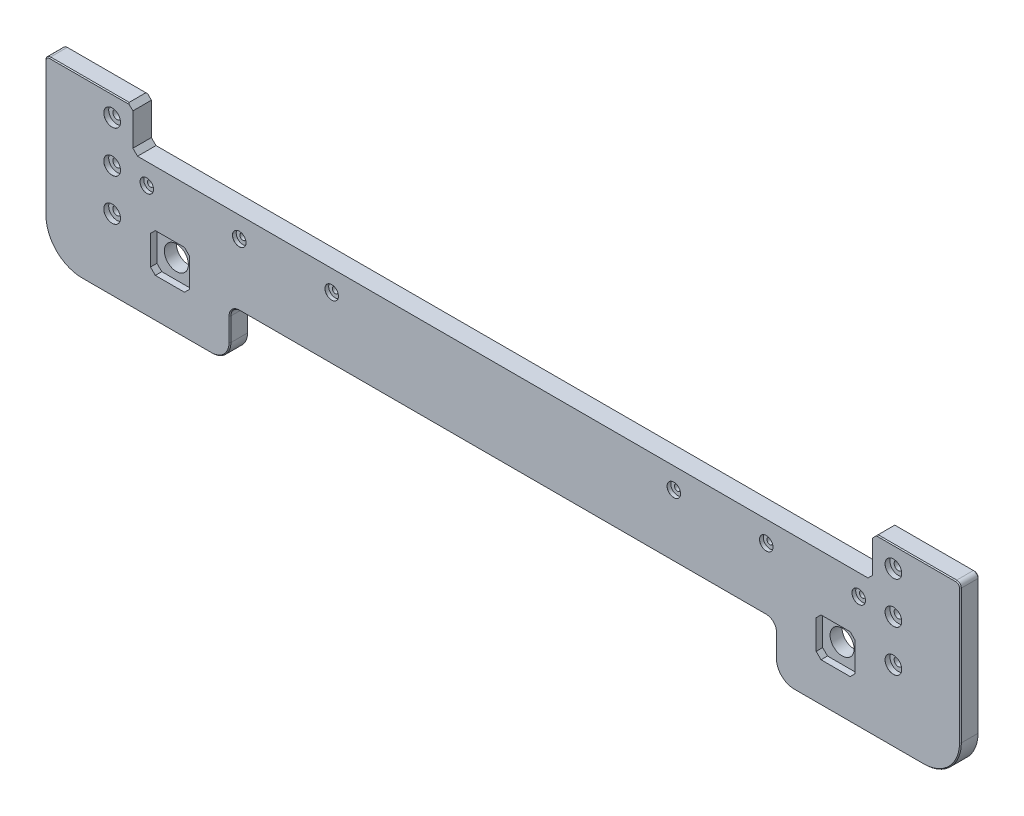
SolidWorks part; units mm, degrees
material "6061 Alloy"
ref_plane "Front Plane" through (0, 0, 0) normal (0, 0, 1) x (1, 0, 0)
ref_plane "Top Plane" through (0, 0, 0) normal (0, 1, 0) x (1, 0, 0)
ref_plane "Right Plane" through (0, 0, 0) normal (1, 0, 0) x (0, 0, -1)
sketch "Sketch1" plane through (0, 0, 0) normal (0, 0, 1) x (1, 0, 0)
  line L0 (-495, 33.1177) -> (-495, 178.1177)
  line L1 (-490, 183.1177) -> (-400, 183.1177)
  line L2 (495, 178.1177) -> (495, 33.1177)
  line L3 (455, -6.8823) -> (315, -6.8823)
  line L4 (295, 13.1177) -> (295, 38.1177)
  line L5 (285, 48.1177) -> (-285, 48.1177)
  line L6 (-295, 38.1177) -> (-295, 13.1177)
  line L7 (-315, -6.8823) -> (-455, -6.8823)
  line L8 (0, 183.1177) -> (0, -96.8627) construction
  line L10 (0, 138.1177) -> (-400, 138.1177)
  line L11 (-400, 138.1177) -> (-400, 183.1177)
  line L12 (0, 138.1177) -> (400, 138.1177)
  line L13 (400, 138.1177) -> (400, 183.1177)
  line L14 (400, 183.1177) -> (490, 183.1177)
  arc A0 (-285, 48.1177) -> (-295, 38.1177) centre (-285, 38.1177) ccw
  arc A1 (295, 38.1177) -> (285, 48.1177) centre (285, 38.1177) ccw
  arc A2 (495, 33.1177) -> (455, -6.8823) centre (455, 33.1177) cw
  arc A3 (-495, 33.1177) -> (-455, -6.8823) centre (-455, 33.1177) ccw
  arc A4 (315, -6.8823) -> (295, 13.1177) centre (315, 13.1177) cw
  arc A5 (-295, 13.1177) -> (-315, -6.8823) centre (-315, 13.1177) cw
  arc A6 (490, 183.1177) -> (495, 178.1177) centre (490, 178.1177) cw
  arc A7 (-495, 178.1177) -> (-490, 183.1177) centre (-490, 178.1177) cw
  point P11 (-445, 183.1177)
  point P20 (495, -6.8823)
  point P23 (-495, -6.8823)
  point P26 (295, -6.8823)
  point P29 (-295, -6.8823)
  point P32 (495, 183.1177)
  point P35 (-495, 183.1177)
  dimension "D1" = 990
  dimension "D8" = 10
  dimension "D9" = 10
  dimension "D10" = 40
  dimension "D11" = 20
  dimension "D12" = 5
  dimension "D2" = 45
  dimension "D3" = 190
  dimension "D4" = 190
  dimension "D5" = 200
  dimension "D6" = 200
  dimension "D7" = 495
  dimension "D13" = 135
extrude "Boss-Extrude1" add sketch "Sketch1" along normal blind 20
hole_wizard "1 Rc Tapped Hole1" positions "Sketch2" profile "Sketch4" size "1" standard "DIN"
sketch "Sketch2" plane through (0, 0, 20) normal (0, 0, 1) x (1, 0, 0)
  point P0 (395.4554, 41.9732)
sketch "Sketch4" plane through (395.4554, 41.9732, 20) normal (1, 0, 0) x (0, -1, 0)
  line L0 (0, 0) -> (0, 20)
  line L1 (0, 20) -> (13.5, 20)
  line L3 (13.5, 20) -> (13.5, 19)
  line L4 (13.5, 19) -> (16.0322, 19)
  line L5 (16.0322, 19) -> (16.6245, 0.025)
  line L6 (16.6245, 0.025) -> (16.6495, 0)
  line L7 (16.6495, 0) -> (0, 0)
  line L8 (0, -6.35) -> (0, 107.95) construction
  line L9 (-16.6245, 0.025) -> (-16.6495, 0) construction
  line L11 (-13.5, 19) -> (-16.0322, 19) construction
  line L12 (-16.0322, 19) -> (-16.6245, 0.025) construction
  dimension "Thru Tap Drill Dia." = 27
  dimension "Thru Tap Drill Depth" = 20
  dimension "Thread Dia." = 33.249
  dimension "Thread Angle" = 3.576
  dimension "Thread Depth" = 19
  dimension "Near C'Sink Dia." = 33.299
  dimension "Near C'Sink Angle" = 90
hole_wizard "CBORE for M8 Hex Head Bolt1" positions "Sketch5" profile "Sketch6" counterbore size "M8" standard "DIN" end condition up to next
sketch "Sketch5" plane through (0, 0, 20) normal (0, 0, 1) x (1, 0, 0)
  line L0 (-400, 183.1177) -> (-490, 183.1177) construction
  point P0 (-422.5, 160.6177)
  point P2 (-422.5, 115.6177)
  point P10 (-1342.1281, 1089.9069)
  point P18 (-422.5, 70.6177)
  dimension "D2" = 422.5
  dimension "D3" = 22.5
  dimension "D4" = 45
  dimension "D5" = 45
sketch "Sketch6" plane through (-422.5, 160.6177, 20) normal (1, 0, 0) x (0, -1, 0)
  line L0 (0, 0) -> (0, 20)
  line L1 (0, 20) -> (4.5, 20)
  line L3 (4.5, 20) -> (4.5, 5.3)
  line L4 (9.0055, 5.3) -> (4.5, 5.3)
  line L5 (9.0055, 5.3) -> (9.0055, 0.025)
  line L6 (9.0055, 0.025) -> (9.0305, 0)
  line L7 (9.0305, 0) -> (0, 0)
  line L8 (-9.0055, 0.025) -> (-9.0305, 0) construction
  line L11 (0, -6.35) -> (0, 107.95) construction
  dimension "Thru Hole Dia." = 9
  dimension "Thru Hole Depth" = 20
  dimension "C'Bore Dia." = 18.011
  dimension "C'Bore Depth" = 5.3
  dimension "Near C'Sink Dia." = 18.061
  dimension "Near C'Sink Angle" = 90
mirror "Mirror1" about plane through (0, 0, 0) normal (1, 0, 0) of "CBORE for M8 Hex Head Bolt1"
hole_wizard "CBORE for M6 Hex Head Bolt1" positions "Sketch7" profile "Sketch8" counterbore size "M6" standard "DIN" end condition up to next
sketch "Sketch7" plane through (0, 0, 20) normal (0, 0, 1) x (1, 0, 0)
  line L0 (0, -55) -> (0, 55) construction
  line L1 (-400, 183.1177) -> (-490, 183.1177) construction
  point P0 (-385, 115.6177)
  point P2 (-285, 115.6177)
  point P4 (-185.0029, 115.6177)
  dimension "D1" = 385
  dimension "D4" = 67.5
sketch "Sketch8" plane through (-385, 115.6177, 20) normal (1, 0, 0) x (0, -1, 0)
  line L0 (0, 0) -> (0, 20.001)
  line L1 (0, 20.001) -> (3.3, 20.001)
  line L3 (3.3, 20.001) -> (3.3, 4)
  line L4 (7.2735, 4) -> (3.3, 4)
  line L5 (7.2735, 4) -> (7.2735, 0.025)
  line L6 (7.2735, 0.025) -> (7.2985, 0)
  line L7 (7.2985, 0) -> (0, 0)
  line L8 (-7.2735, 0.025) -> (-7.2985, 0) construction
  line L11 (0, -6.35) -> (0, 107.95) construction
  dimension "Thru Hole Dia." = 6.6
  dimension "Thru Hole Depth" = 20.001
  dimension "C'Bore Dia." = 14.547
  dimension "C'Bore Depth" = 4
  dimension "Near C'Sink Dia." = 14.597
  dimension "Near C'Sink Angle" = 90
mirror "Mirror2" about plane through (0, 0, 0) normal (1, 0, 0) of "CBORE for M6 Hex Head Bolt1"
sketch "Sketch16" plane through (0, 0, 20) normal (0, 0, 1) x (1, 0, 0)
  line L0 (-495, 178.1177) -> (-495, 33.1177) construction
  line L1 (-375.7732, 78.1177) -> (-344.2293, 78.1177)
  line L2 (-381, 72.8837) -> (-381, 41.3493)
  line L3 (-375.7707, 36.1177) -> (-344.2268, 36.1177)
  line L4 (-339, 72.8861) -> (-339, 41.3518)
  line L6 (-381, 72.8837) -> (-375.7732, 78.1177)
  line L7 (-344.2268, 36.1177) -> (-339, 41.3518)
  line L8 (-381, 41.3493) -> (-375.7707, 36.1177)
  line L9 (-344.2293, 78.1177) -> (-339, 72.8861)
  line L10 (-400, 183.1177) -> (-490, 183.1177) construction
  dimension "D1" = 114
  dimension "D2" = 42
  dimension "D3" = 42
  dimension "D4" = 105
  dimension "D5" = 52
  dimension "D6" = 52
chamfer "Chamfer1" distance 1 angle 45 17 edges at (495, 105.6177, 20) (385, -6.8823, 20) (295, 25.6177, 20) (0, 48.1177, 20) (-295, 25.6177, 20) (-385, -6.8823, 20) (-495, 105.6177, 20) (-445, 183.1177, 20) (-292.0711, 45.1888, 20) (292.0711, 45.1888, 20) (483.2843, 4.8334, 20) (-483.2843, 4.8334, 20) (300.8579, -1.0244, 20) (-300.8579, -1.0244, 20) (493.5355, 181.6532, 20) (-493.5355, 181.6532, 20) (445, 183.1177, 20)
chamfer "Chamfer2" distance 1 angle 45 17 edges at (385, -6.8823, 0) (295, 25.6177, 0) (0, 48.1177, 0) (-295, 25.6177, 0) (-385, -6.8823, 0) (-495, 105.6177, 0) (-445, 183.1177, 0) (495, 105.6177, 0) (-292.0711, 45.1888, 0) (292.0711, 45.1888, 0) (-483.2843, 4.8334, 0) (483.2843, 4.8334, 0) (-300.8579, -1.0244, 0) (300.8579, -1.0244, 0) (-493.5355, 181.6532, 0) (493.5355, 181.6532, 0) (445, 183.1177, 0)
extrude "Cut-Extrude14" cut sketch "Sketch16" against normal blind 7
sketch "Sketch49" plane through (0, 0, 20) normal (0, 0, 1) x (1, 0, 0)
  line L0 (-344.2293, 78.1177) -> (-375.7732, 78.1177) construction
  line L1 (-381, 72.8837) -> (-381, 41.3493) construction
  circle A0 centre (-360, 57.1177) radius 13
  point P0 (-360, 57.1177)
  dimension "D3" = 13
  dimension "D1" = 21
  dimension "D2" = 21
extrude "Cut-Extrude15" cut sketch "Sketch49" against normal through all
mirror "Mirror3" about plane through (0, 0, 0) normal (1, 0, 0) of "Cut-Extrude15", "Cut-Extrude14"
fillet "Fillet1" radius 5 4 edges at (-400, 138.1177, 10) (-400, 183.1177, 10) (400, 183.1177, 10) (400, 138.1177, 10) profile chamfer
equation "\"Lx_Alu_Profile_45x45H_Tuli\"= 800"
